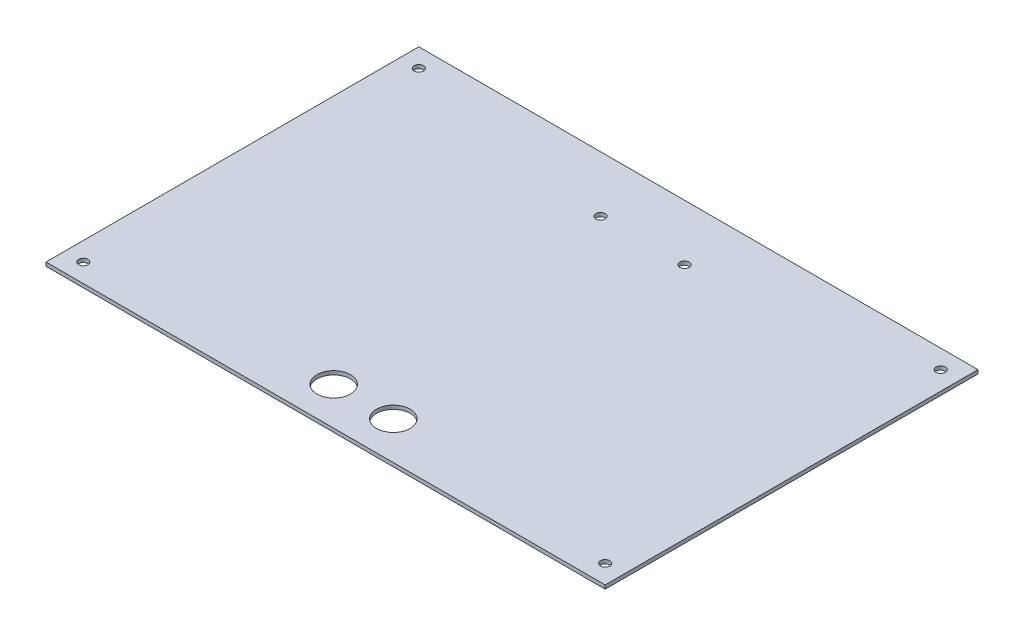
SolidWorks part; units mm, degrees
material "ABS"
ref_plane "Plano frontal" through (0, 0, 0) normal (0, 0, 1) x (1, 0, 0)
ref_plane "Plano superior" through (0, 0, 0) normal (0, 1, 0) x (1, 0, 0)
ref_plane "Plano direito" through (0, 0, 0) normal (1, 0, 0) x (0, 0, -1)
sketch "Esboço1" plane through (0, 0, 0) normal (0, 1, 0) x (1, 0, 0)
  line L0 (-64.0948, 25.037) -> (235.9052, 25.037)
  line L1 (-64.0948, -174.963) -> (235.9052, -174.963)
  line L2 (-64.0948, 25.037) -> (-64.0948, -174.963)
  line L4 (235.9052, 25.037) -> (235.9052, -174.963)
  circle A0 centre (-54.0948, 15.037) radius 2.5
  circle A1 centre (225.9052, 15.037) radius 2.5
  circle A2 centre (225.9052, -164.963) radius 2.5
  circle A3 centre (-54.0948, -164.963) radius 2.5
  circle A4 centre (63.4052, -4.963) radius 2.5
  circle A5 centre (108.4052, -4.963) radius 2.5
  circle A6 centre (101.9052, -154.6184) radius 9
  circle A7 centre (69.9052, -154.6184) radius 9
  dimension "D3" = 5
  dimension "D4" = 5
  dimension "D5" = 5
  dimension "D6" = 5
  dimension "D8" = 5
  dimension "D9" = 5
  dimension "D13" = 18
  dimension "D1" = 300
  dimension "D2" = 200
extrude "Ressalto-extrusão2" add sketch "Esboço1" along normal blind 2 contours L4 L1 L2 L0 | A6 | A7 | A3 | A0 | A4 | A5 | A2 | A1
